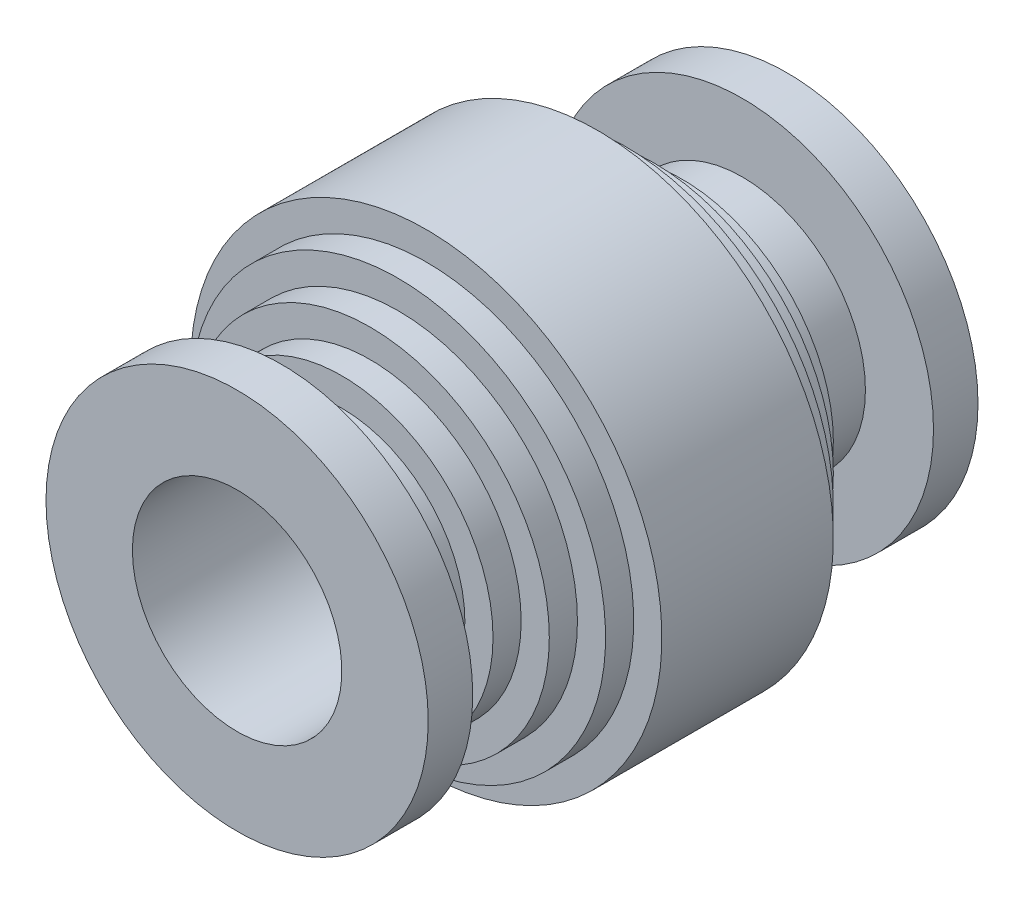
SolidWorks part; units mm, degrees
material "Natural Rubber"
ref_plane "Front Plane" through (0, 0, 0) normal (0, 0, 1) x (1, 0, 0)
ref_plane "Top Plane" through (0, 0, 0) normal (0, 1, 0) x (1, 0, 0)
ref_plane "Right Plane" through (0, 0, 0) normal (1, 0, 0) x (0, 0, -1)
sketch "Sketch1" plane through (0, 0, 0) normal (0, 1, 0) x (1, 0, 0)
  line L0 (0, 0) -> (0, 42.7092) construction
  line L1 (4, 0) -> (50.0896, 0) construction
  line L2 (4, 0) -> (7.3, 0)
  line L3 (7.3, 0) -> (7.3, 1.7)
  line L4 (7.3, 1.7) -> (4.7, 1.7)
  line L5 (4.7, 1.7) -> (4.7, 4)
  line L6 (4.7, 4) -> (5.775, 4)
  line L7 (5.775, 4) -> (5.775, 5.075)
  line L8 (5.775, 5.075) -> (6.85, 5.075)
  line L9 (6.85, 5.075) -> (6.85, 6.15)
  line L10 (6.85, 6.15) -> (7.925, 6.15)
  line L11 (7.925, 6.15) -> (7.925, 7.225)
  line L12 (0, 10.5) -> (2.9881, 10.5) construction
  line L13 (7.925, 14.85) -> (7.925, 13.775)
  line L14 (6.85, 14.85) -> (7.925, 14.85)
  line L15 (6.85, 15.925) -> (6.85, 14.85)
  line L16 (5.775, 15.925) -> (6.85, 15.925)
  line L17 (5.775, 17) -> (5.775, 15.925)
  line L18 (4.7, 17) -> (5.775, 17)
  line L19 (4.7, 19.3) -> (4.7, 17)
  line L20 (7.3, 19.3) -> (4.7, 19.3)
  line L21 (7.3, 21) -> (7.3, 19.3)
  line L22 (7.3, 21) -> (4, 21)
  line L23 (0, 15) -> (0, 0) construction
  line L24 (4, 21) -> (4, 0)
  line L25 (4, 10.5) -> (9, 10.5) construction
  line L26 (7.925, 13.775) -> (9, 13.775)
  line L27 (9, 13.775) -> (9, 12.7)
  line L28 (9, 7.225) -> (9, 8.3)
  line L29 (7.925, 7.225) -> (9, 7.225)
  line L30 (9, 8.3) -> (9, 12.7)
  dimension "D2" = 1.7
  dimension "D1" = 21
  dimension "D3" = 4
  dimension "D4" = 7.3
  dimension "D6" = 9
  dimension "D7" = 4.7
  dimension "D8" = 2.3
revolve "Revolve1" add sketch "Sketch1" angle 360 about L23
